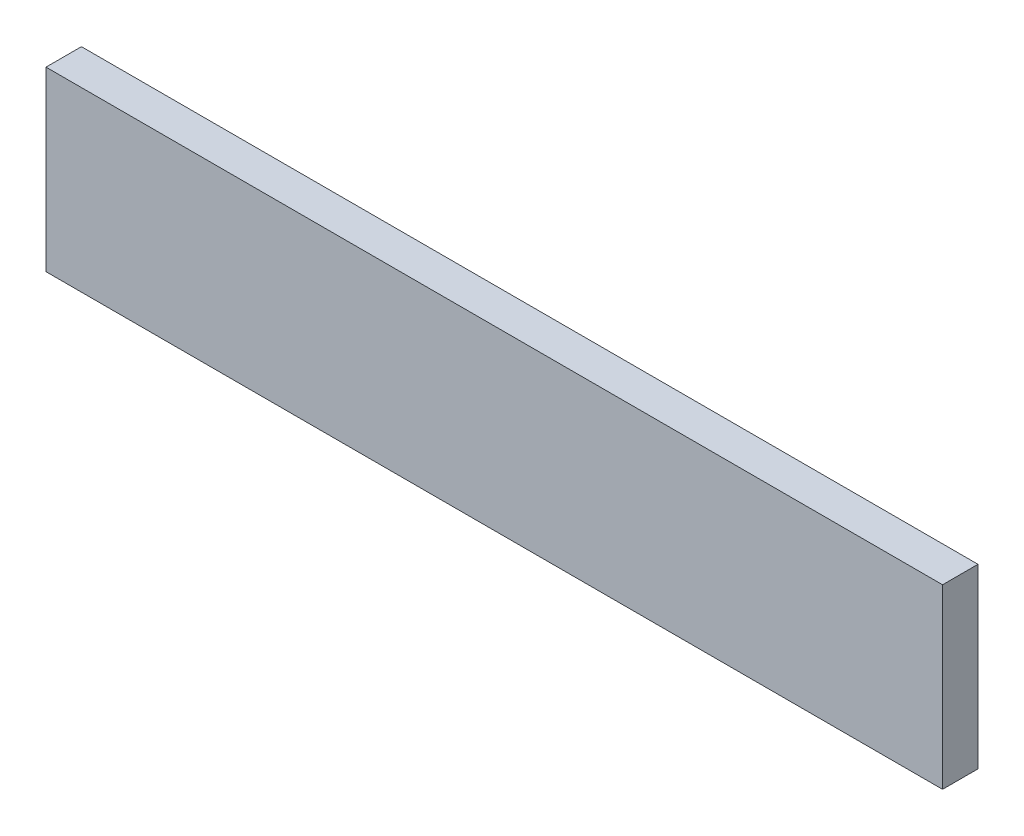
SolidWorks part; units mm, degrees
ref_plane "Front Plane" through (0, 0, 0) normal (0, 0, 1) x (1, 0, 0)
ref_plane "Top Plane" through (0, 0, 0) normal (0, 1, 0) x (1, 0, 0)
ref_plane "Right Plane" through (0, 0, 0) normal (1, 0, 0) x (0, 0, -1)
sketch "Sketch1" plane through (0, 0, 0) normal (0, 0, 1) x (1, 0, 0)
  line L1 (0, 0) -> (506, 0)
  line L2 (0, 0) -> (0, 100)
  line L3 (0, 100) -> (506, 100)
  line L4 (506, 0) -> (506, 100)
  dimension "D1" = 506
  dimension "D2" = 100
extrude "Boss-Extrude1" add sketch "Sketch1" along normal blind 20
